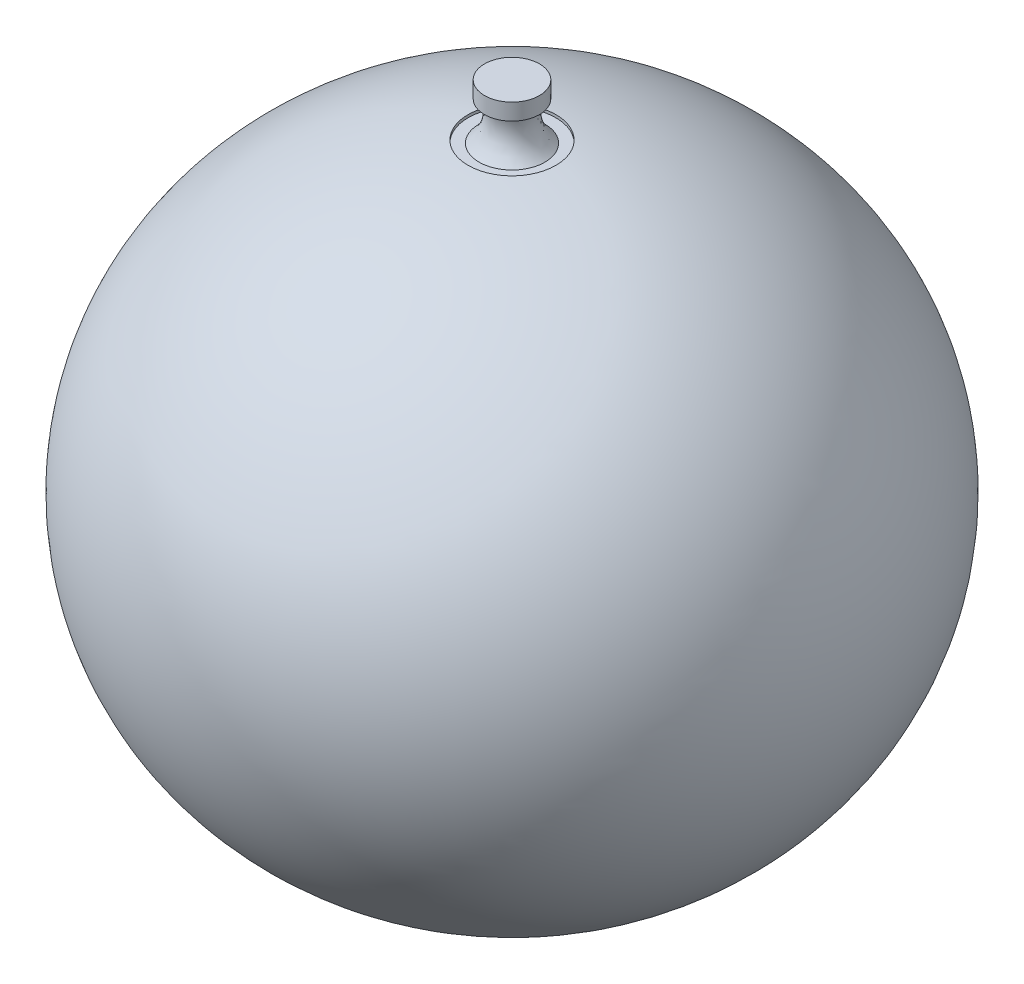
SolidWorks part; units mm, degrees
ref_plane "前视基准面" through (0, 0, 0) normal (0, 0, 1) x (1, 0, 0)
ref_plane "上视基准面" through (0, 0, 0) normal (0, 1, 0) x (1, 0, 0)
ref_plane "右视基准面" through (0, 0, 0) normal (1, 0, 0) x (0, 0, -1)
sketch "草图2" plane through (0, 0, 0) normal (0, 0, 1) x (1, 0, 0)
  line L0 (0, 28) -> (0, -28)
  ellipse E0 centre (0, 0) end of major axis (30, 0) minor radius 28 (0, -28) -> (0, 28) ccw
revolve "旋转1" add sketch "草图2" angle 360 about L0
ref_plane "基准面1" through (0, 28, 0) normal (0, 1, 0) x (1, 0, 0)
sketch "草图9" plane through (0, 28, 0) normal (0, 1, 0) x (1, 0, 0)
  circle A0 centre (0, 0) radius 4
extrude "切除-拉伸3" cut sketch "草图9" against normal blind 0.5
sketch "草图10" plane through (0, 0, 0) normal (0, 0, 1) x (1, 0, 0)
  line L0 (0, 27.5) -> (3, 27.5)
  line L1 (4, 27.5) -> (-4, 27.5) construction
  line L2 (0, 27.5) -> (0, 32.5)
  line L3 (0, 32.5) -> (2.5, 32.5)
  line L4 (2.5, 32.5) -> (2.5, 31)
  line L5 (2.5, 31) -> (2, 31)
  spline S0 degree 2 poles (2, 31) (1.4287, 28.92) (3, 27.5) knots 0 0 0 1 1 1
revolve "旋转2" add sketch "草图10" angle 360 about L2
sketch "草图11" plane through (0, 0, 0) normal (0, 0, 1) x (1, 0, 0)
  line L0 (0, 20) -> (0, -20)
  arc A0 (0, -20) -> (0, 20) centre (0, 0) ccw
revolve "切除-旋转1" cut sketch "草图11" angle 360 about L0
